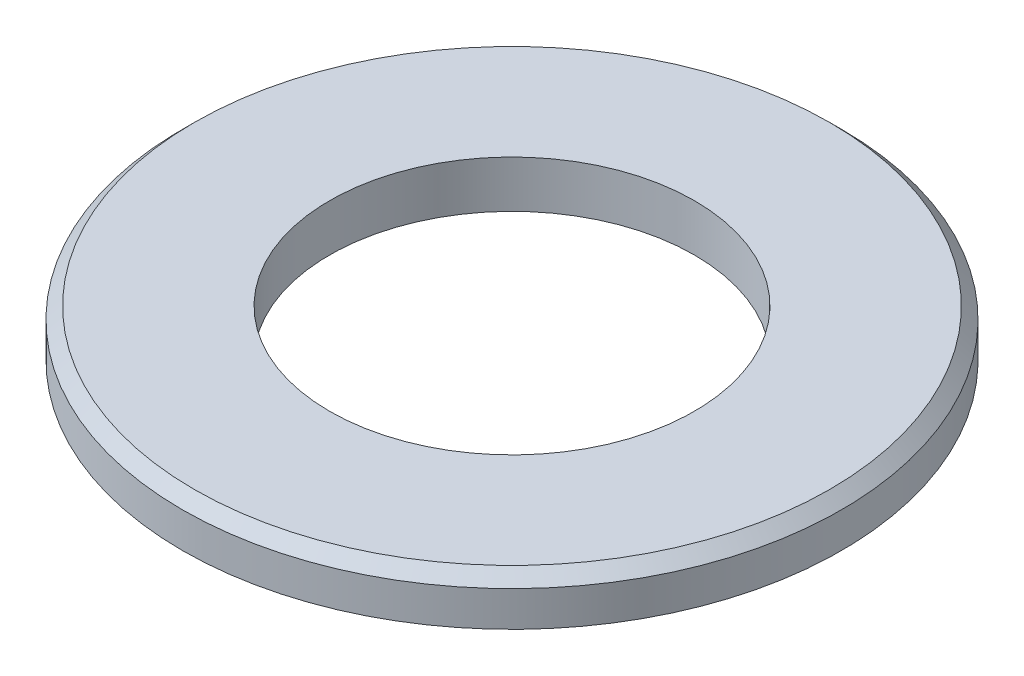
SolidWorks part; units mm, degrees
ref_plane "基准面1" through (0, 0, 0) normal (0, 0, 1) x (1, 0, 0)
ref_plane "基准面2" through (0, 0, 0) normal (0, 1, 0) x (1, 0, 0)
ref_plane "基准面3" through (0, 0, 0) normal (1, 0, 0) x (0, 0, -1)
sketch "尺寸草图" plane through (0, 0, 0) normal (0, 0, 1) x (1, 0, 0)
  line L0 (0, 0) -> (9.1, 0)
  point P3 (4, 0)
  point P4 (56, 0)
  point P5 (31, 0)
  dimension "h" = 4
  dimension "d2" = 56
  dimension "d1" = 31
sketch "草图1" plane through (0, 0, 0) normal (0, 0, 1) x (1, 0, 0)
  line L0 (0, 0) -> (0, 52.7318) construction
  line L1 (-27, 12.6445) -> (-28, 11.6445)
  line L2 (-15.5, 8.6445) -> (-28, 8.6445)
  line L3 (-15.5, 8.6445) -> (-15.5, 12.6445)
  line L4 (-15.5, 12.6445) -> (-27, 12.6445)
  line L5 (-28, 8.6445) -> (-28, 11.6445)
  point P4 (-28, 12.6445)
  dimension "h" = 4
  dimension "D1" = 15.5
  dimension "D2" = 28
revolve "基体-旋转" add sketch "草图1" angle 360 about L0
equation "\"h@草图1\" = \"h@尺寸草图\""
equation "\"D1@草图1\" = \"d1@尺寸草图\" / 2"
equation "\"D2@草图1\" = \"d2@尺寸草图\" / 2"
equation "\"D5@草图1\" = \"h@草图1\" *0.25"
